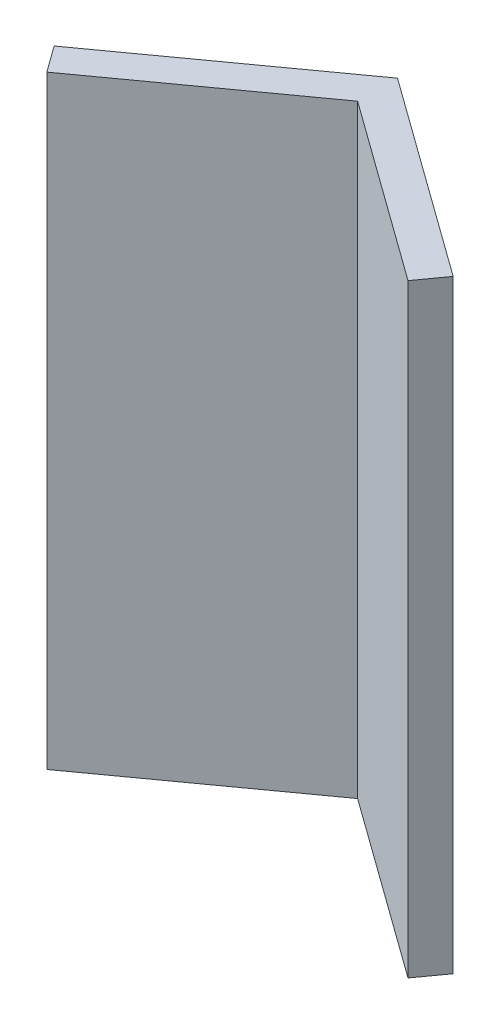
SolidWorks part; units mm, degrees
ref_plane "Front Plane" through (0, 0, 0) normal (0, 0, 1) x (1, 0, 0)
ref_plane "Top Plane" through (0, 0, 0) normal (0, 1, 0) x (1, 0, 0)
ref_plane "Right Plane" through (0, 0, 0) normal (1, 0, 0) x (0, 0, -1)
sketch "Sketch1" plane through (0, 31.4537, 0) normal (0, 1, 0) x (1, 0, 0)
  line L0 (39.8007, -21.9665) -> (-10.1993, -21.9665) construction
  line L1 (14.8007, -6.4676) -> (14.8007, -106.4676) construction
  line L2 (-1.945, -163.3832) -> (14.8007, -151.3116)
  line L3 (14.8007, -151.3116) -> (31.5463, -163.3832)
  line L4 (31.5463, -163.3832) -> (33.3007, -160.9496)
  line L5 (33.3007, -160.9496) -> (14.8007, -147.6133)
  line L6 (14.8007, -147.6133) -> (-3.6993, -160.9496)
  line L7 (-3.6993, -160.9496) -> (-1.945, -163.3832)
  line L9 (14.8007, -175.9665) -> (3.1052, -159.7426) construction
  line L10 (14.8007, -175.9665) -> (26.4962, -159.7426) construction
  circle A0 centre (14.8007, -175.9665) radius 20 construction
  dimension "D1" = 40
  dimension "D2" = 154
  dimension "D3" = 0
  dimension "D4" = 3
  dimension "D5" = 90
  dimension "D6" = 0
  dimension "D7" = 0
  dimension "D8" = 3
  dimension "D9" = 37
  dimension "D10" = 71.574
extrude "Boss-Extrude1" add sketch "Sketch1" along normal blind 43.5 and the other way blind 12.5 contours L6 L7 L2 L3 L4 L5
